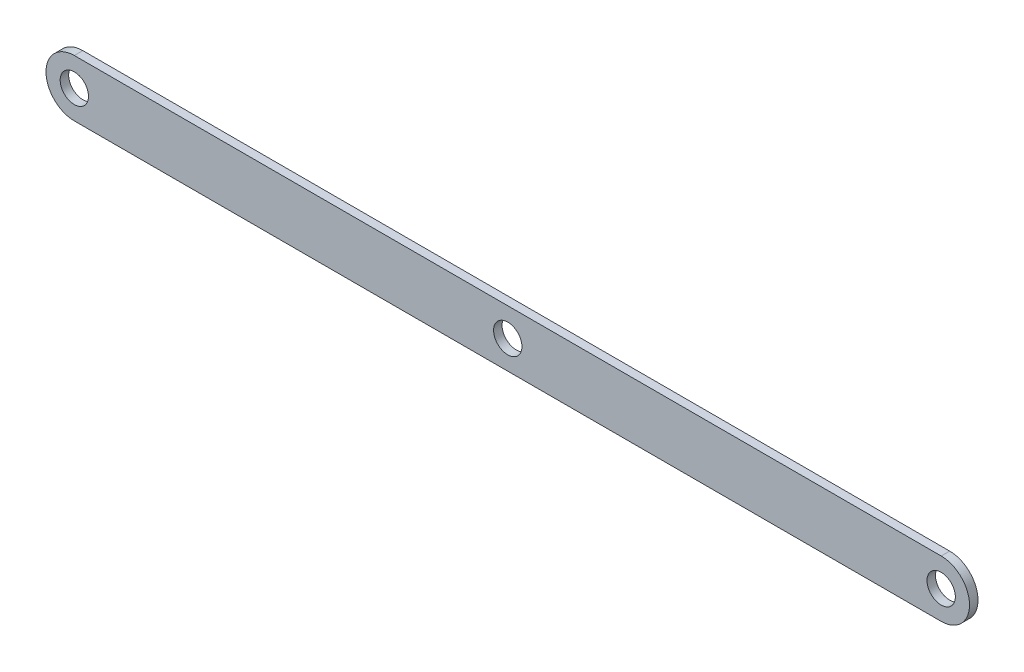
SolidWorks part; units mm, degrees
material "Alloy Steel"
ref_plane "Front Plane" through (0, 0, 0) normal (0, 0, 1) x (1, 0, 0)
ref_plane "Top Plane" through (0, 0, 0) normal (0, 1, 0) x (1, 0, 0)
ref_plane "Right Plane" through (0, 0, 0) normal (1, 0, 0) x (0, 0, -1)
sketch "Sketch1" plane through (0, 0, 0) normal (0, 0, 1) x (1, 0, 0)
  line L0 (0, 0) -> (153, 0) construction
  line L1 (0, 5) -> (153, 5)
  line L2 (0, -5) -> (153, -5)
  arc A0 (0, 5) -> (0, -5) centre (0, 0) ccw
  arc A1 (153, -5) -> (153, 5) centre (153, 0) ccw
  circle A2 centre (0, 0) radius 2.5
  circle A3 centre (153, 0) radius 2.5
  circle A4 centre (76.5, 0) radius 2.5
  point P3 (76.5, 0)
  dimension "D3" = 5
  dimension "D1" = 10
  dimension "D2" = 153
extrude "Boss-Extrude1" add sketch "Sketch1" along normal blind 1.5
